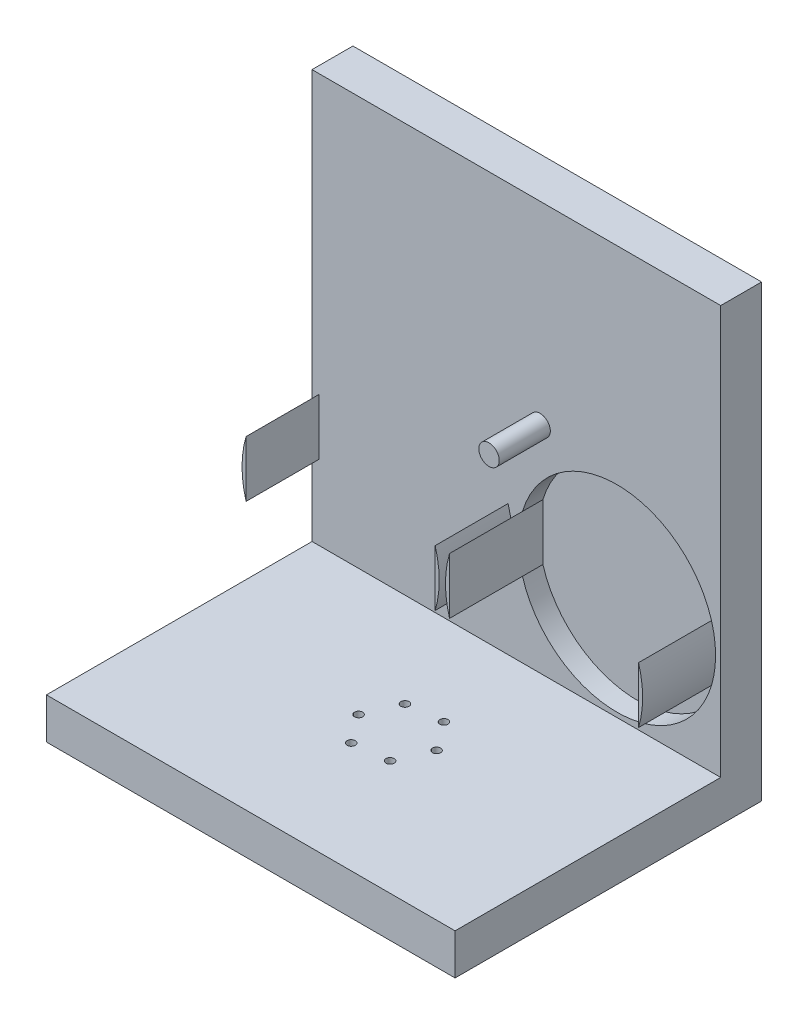
SolidWorks part; units mm, degrees
ref_plane "前视基准面" through (0, 0, 0) normal (0, 0, 1) x (1, 0, 0)
ref_plane "上视基准面" through (0, 0, 0) normal (0, 1, 0) x (1, 0, 0)
ref_plane "右视基准面" through (0, 0, 0) normal (1, 0, 0) x (0, 0, -1)
sketch "草图1" plane through (0, 0, 0) normal (0, 0, 1) x (1, 0, 0)
  line L1 (-101.8379, 99.4682) -> (98.1621, 99.4682)
  line L2 (-101.8379, 99.4682) -> (-101.8379, -100.5318)
  line L3 (-101.8379, -100.5318) -> (98.1621, -100.5318)
  line L4 (98.1621, 99.4682) -> (98.1621, -100.5318)
extrude "凸台-拉伸2" add sketch "草图1" along normal blind 20
sketch "草图4" plane through (0, 0, 20) normal (0, 0, 1) x (1, 0, 0)
  line L0 (-16.3978, 91.0901) -> (11.0977, 91.0901)
  line L1 (-16.3978, -1.4099) -> (11.0977, -1.4099)
  line L2 (1.1474, -36.2889) -> (1.1474, -63.7844)
  line L3 (93.6474, -36.2889) -> (93.6474, -63.7844)
  circle A0 centre (-2.6501, 44.8401) radius 48.25
  circle A1 centre (47.3974, -50.0367) radius 48.25
  dimension "D1" = 92.5
  dimension "D2" = 96.5
  dimension "D4" = 96.5
  dimension "D3" = 92.5
sketch "草图5" plane through (0, 0, 20) normal (0, 0, 1) x (1, 0, 0)
  line L0 (-16.3978, 91.0901) -> (11.0977, 91.0901) construction
  line L1 (-16.3978, -1.4099) -> (11.0977, -1.4099) construction
  line L2 (-16.3978, 91.0901) -> (11.0977, 91.0901)
  line L3 (11.0977, -1.4099) -> (-16.3978, -1.4099)
  arc A0 (-16.3978, 91.0901) -> (11.0977, 91.0901) centre (-2.6501, 44.8401) cw
  arc A1 (11.0977, -1.4099) -> (-16.3978, -1.4099) centre (-2.6501, 44.8401) cw
sketch "草图7" plane through (0, 0, 20) normal (0, 0, 1) x (1, 0, 0)
  line L0 (1.1474, -36.2889) -> (1.1474, -63.7844) construction
  line L1 (93.6474, -36.2889) -> (93.6474, -63.7844) construction
  line L2 (1.1474, -36.2889) -> (1.1474, -63.7844)
  line L3 (93.6474, -36.2889) -> (93.6474, -63.7844)
  arc A0 (1.1474, -36.2889) -> (1.1474, -63.7844) centre (47.3974, -50.0367) ccw
  arc A1 (93.6474, -36.2889) -> (93.6474, -63.7844) centre (47.3974, -50.0367) cw
extrude "凸台-拉伸5" add sketch "草图7" along normal blind 35.7
sketch "草图10" plane through (0, 0, 20) normal (0, 0, 1) x (1, 0, 0)
  line L0 (-98.4014, -36.4686) -> (-98.4014, -63.9641)
  line L1 (-5.9014, -36.4686) -> (-5.9014, -63.9641)
  circle A0 centre (-52.1514, -50.2164) radius 48.25
  dimension "D1" = 92.5
  dimension "D2" = 96.5
sketch "草图11" plane through (0, 0, 20) normal (0, 0, 1) x (1, 0, 0)
  line L0 (-98.4014, -36.4686) -> (-98.4014, -63.9641) construction
  line L1 (-5.9014, -36.4686) -> (-5.9014, -63.9641) construction
  line L2 (-98.4014, -36.4686) -> (-98.4014, -63.9641)
  line L3 (-5.9014, -36.4686) -> (-5.9014, -63.9641)
  arc A0 (-98.4014, -36.4686) -> (-98.4014, -63.9641) centre (-52.1514, -50.2164) ccw
  arc A1 (-5.9014, -36.4686) -> (-5.9014, -63.9641) centre (-52.1514, -50.2164) cw
extrude "凸台-拉伸7" add sketch "草图11" along normal blind 35.7
sketch "草图14" plane through (0, 0, 20) normal (0, 0, 1) x (1, 0, 0)
  line L0 (93.6474, -36.2889) -> (93.6474, -63.7844) construction
  line L1 (1.1474, -36.2889) -> (1.1474, -63.7844)
  line L2 (93.6474, -36.2889) -> (93.6474, -63.7844)
  arc A0 (1.1474, -36.2889) -> (93.6474, -36.2889) centre (47.3974, -50.0367) cw
  arc A1 (1.1474, -63.7844) -> (93.6474, -63.7844) centre (47.3974, -50.0367) ccw
sketch "草图16" plane through (0, 0, 20) normal (0, 0, 1) x (1, 0, 0)
  line L1 (-101.8379, -100.5318) -> (98.1621, -100.5318)
  line L2 (-101.8379, -100.5318) -> (-101.8379, -120.5318)
  line L3 (-101.8379, -120.5318) -> (98.1621, -120.5318)
  line L4 (98.1621, -100.5318) -> (98.1621, -120.5318)
extrude "凸台-拉伸9" add sketch "草图16" along normal blind 130 separate body
sketch "草图17" plane through (98.1621, 0, 0) normal (1, 0, 0) x (0, 0, -1)
  line L1 (-20, -100.5318) -> (0, -100.5318)
  line L2 (-20, -100.5318) -> (-20, -120.5296)
  line L3 (-20, -120.5296) -> (0, -120.5296)
  line L4 (0, -100.5318) -> (0, -120.5296)
extrude "凸台-拉伸10" add sketch "草图17" against normal blind 200
sketch "草图18" plane through (0, -100.5318, 0) normal (0, 1, 0) x (1, 0, 0)
  line L0 (-16.3978, -20) -> (11.0977, -20) construction
  circle A1 centre (-17.1399, -81.9463) radius 2
  circle A2 centre (-10.2555, -66.1296) radius 2
  circle A3 centre (6.8844, -64.1833) radius 2
  circle A4 centre (17.1399, -78.0537) radius 2
  circle A5 centre (10.2555, -93.8704) radius 2
  circle A6 centre (-6.8844, -95.8167) radius 2
  point P17 (0, -80)
  dimension "D1" = 60
  dimension "D3" = 17.25
  dimension "D2" = 6
extrude "切除-拉伸3" cut sketch "草图18" against normal blind 20
extrude "切除-拉伸4" cut sketch "草图14" against normal blind 10
sketch "草图20" plane through (0, 0, 20) normal (0, 0, 1) x (1, 0, 0)
  circle A0 centre (9.7713, 4.5802) radius 5
extrude "凸台-拉伸11" add sketch "草图20" along normal blind 25
